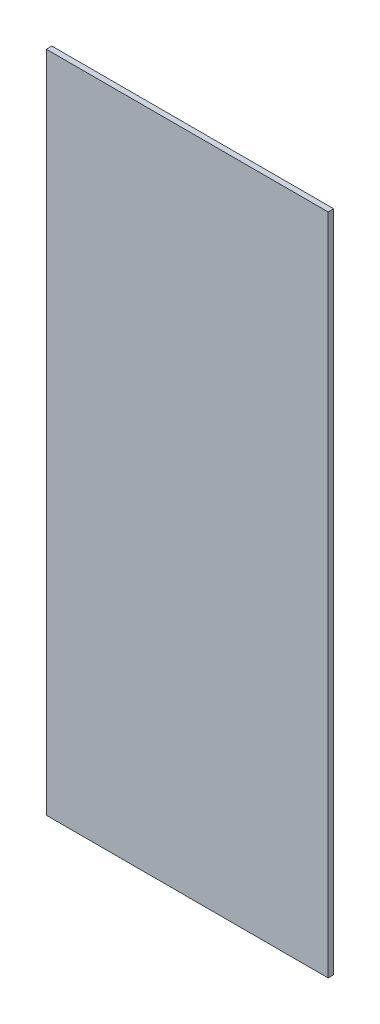
SolidWorks part; units mm, degrees
ref_plane "Front Plane" through (0, 0, 0) normal (0, 0, 1) x (1, 0, 0)
ref_plane "Top Plane" through (0, 0, 0) normal (0, 1, 0) x (1, 0, 0)
ref_plane "Right Plane" through (0, 0, 0) normal (1, 0, 0) x (0, 0, -1)
sketch "Sketch1" plane through (0, 0, 0) normal (0, 0, 1) x (1, 0, 0)
  line L1 (0, 0) -> (-647.7, 0)
  line L2 (0, 0) -> (0, 1524)
  line L3 (0, 1524) -> (-647.7, 1524)
  line L4 (-647.7, 0) -> (-647.7, 1524)
  dimension "D1" = 647.7
  dimension "D2" = 1524
extrude "Boss-Extrude1" add sketch "Sketch1" along normal blind 12.7
sketch "Sketch2" plane through (0, 0, 12.7) normal (0, 0, 1) x (1, 0, 0)
  line L0 (-647.7, 0) -> (0, 0) construction
  line L1 (76.2, 0) -> (-723.9, 0)
  line L2 (76.2, 0) -> (76.2, 825.5)
  line L3 (76.2, 825.5) -> (-723.9, 825.5)
  line L4 (-723.9, 0) -> (-723.9, 825.5)
  line L5 (-323.85, 825.5) -> (-323.85, 1524) construction
  line L6 (0, 1524) -> (-647.7, 1524) construction
  line L7 (-647.7, 1524) -> (-647.7, 0) construction
  dimension "D1" = 76.2
  dimension "D2" = 825.5
extrude "Boss-Extrude2" [suppressed] add sketch "Sketch2" against normal up to surface (12.7 mm away)
